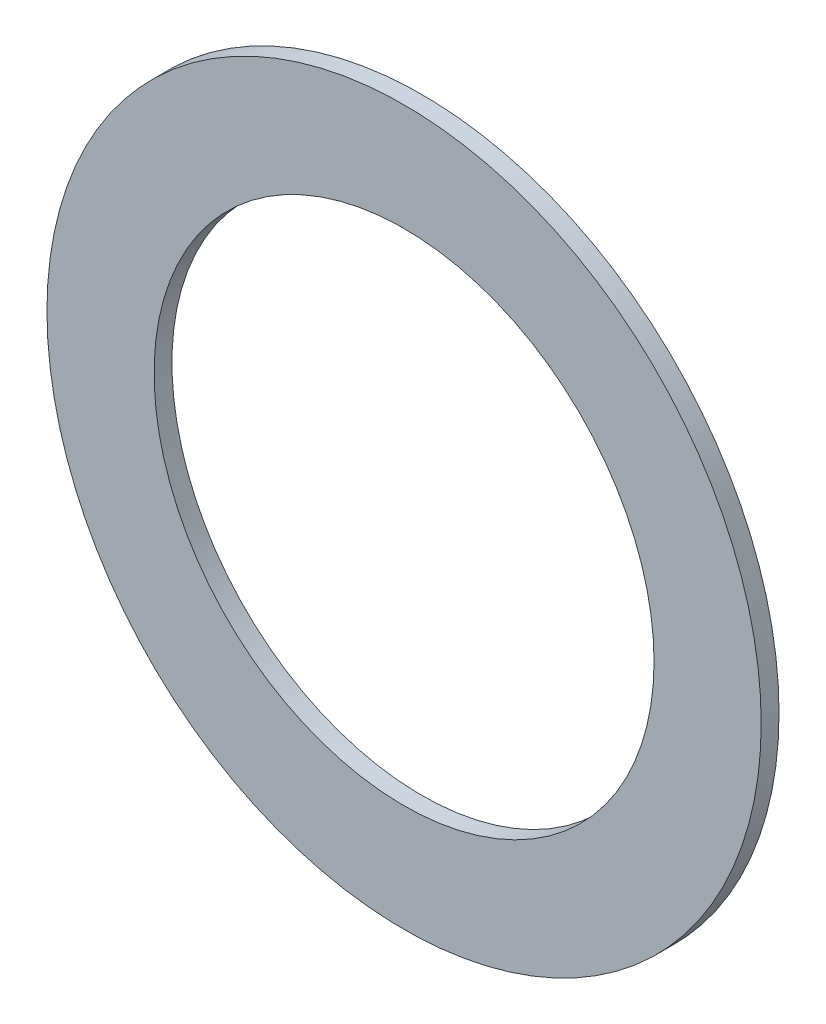
SolidWorks part; units mm, degrees
ref_plane "Front Plane" through (0, 0, 0) normal (0, 0, 1) x (1, 0, 0)
ref_plane "Top Plane" through (0, 0, 0) normal (0, 1, 0) x (1, 0, 0)
ref_plane "Right Plane" through (0, 0, 0) normal (1, 0, 0) x (0, 0, -1)
sketch "Sketch1" plane through (0, 0, 0) normal (0, 0, 1) x (1, 0, 0)
  circle A0 centre (0, 0) radius 31.75
  circle A1 centre (0, 0) radius 22.225
  dimension "OD" = 63.5
  dimension "ID" = 44.45
sketch "Sketch2" plane through (0, 0, 0) normal (1, 0, 0) x (0, 0, -1)
  line L0 (-0.8, 31.75) -> (0.8, 31.75) construction
  line L1 (-0.8, 22.225) -> (0.8, 22.225) construction
  line L2 (-0.8, -22.225) -> (0.8, -22.225) construction
  point P2 (0, 31.75)
  point P8 (0, 22.225)
  point P12 (0, -22.225)
  dimension "Thickness Range" = 1.6
sketch "Sketch3" plane through (0, 0, 0) normal (0, 0, 1) x (1, 0, 0)
  circle A0 centre (0, 0) radius 31.75
  circle A1 centre (0, 0) radius 22.225
  circle A2 centre (0, 0) radius 31.75 construction
  circle A3 centre (0, 0) radius 22.225 construction
extrude "Boss-Extrude1" add sketch "Sketch3" against normal blind 1.5875
